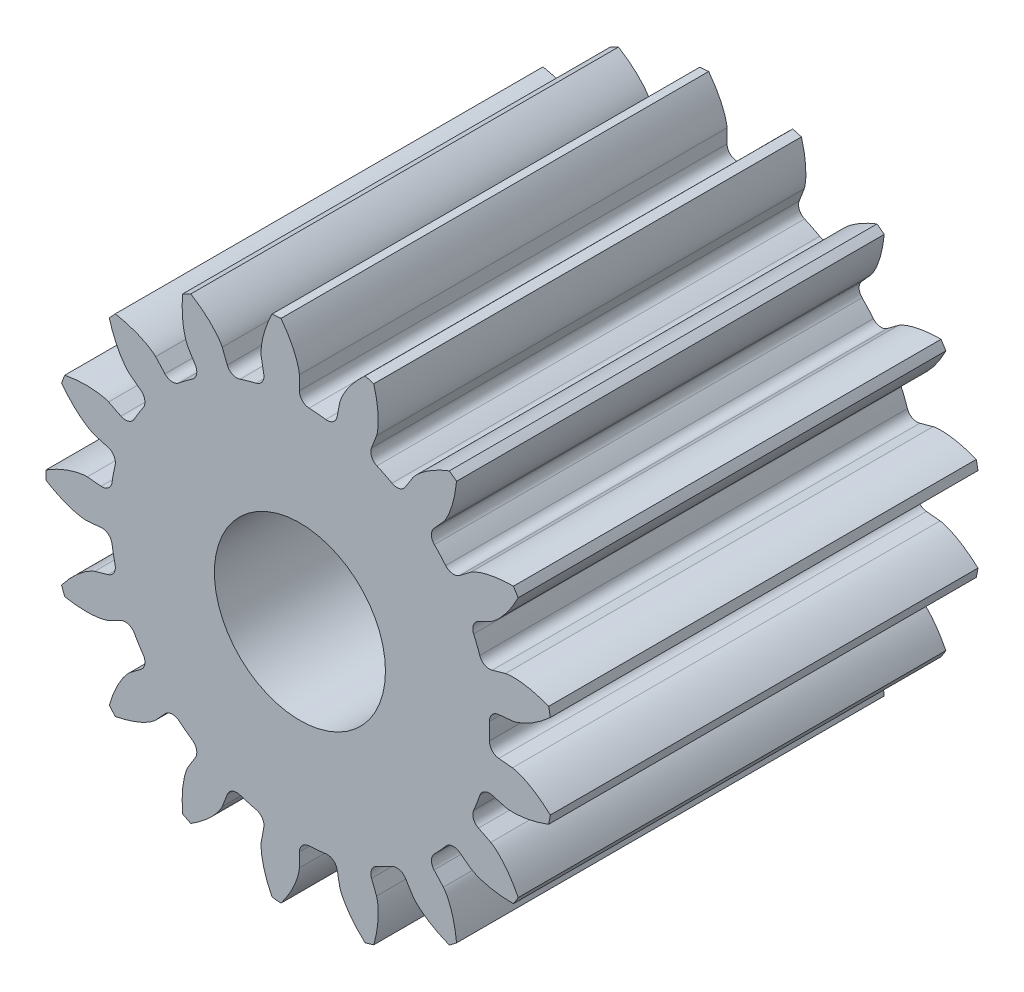
SolidWorks part; units mm, degrees
ref_plane "Front Plane" through (0, 0, 0) normal (0, 0, 1) x (1, 0, 0)
ref_plane "Top Plane" through (0, 0, 0) normal (0, 1, 0) x (1, 0, 0)
ref_plane "Right Plane" through (0, 0, 0) normal (1, 0, 0) x (0, 0, -1)
ref_axis "Gear Axis" through (0, 0, -0.2501) along (0, 0, 1)
sketch "Blank Sketch" plane through (0, 0, 0) normal (0, 0, 1) x (1, 0, 0)
  circle A0 centre (0, 0) radius 11.875
  dimension "OD" = 23.75
extrude "Blank" add sketch "Blank Sketch" along normal blind 20
sketch "Tooth Space Sketch" plane through (0, 0, 0) normal (0, 0, 1) x (1, 0, 0)
  line L0 (9.9391, 0.9485) -> (9.2957, 0.8871)
  line L1 (9.9391, -0.9485) -> (9.2957, -0.8871)
  line L2 (12.7424, 3.1457) -> (12.7424, -3.1457)
  arc A0 (9.2957, 0.8871) -> (8.8663, 0.3932) centre (9.3408, 0.4142) ccw
  arc A1 (8.8663, -0.3932) -> (9.2957, -0.8871) centre (9.3408, -0.4142) ccw
  arc A2 (8.8663, -0.3932) -> (8.8663, 0.3932) centre (0, 0) ccw
  spline S0 degree 4 poles (9.9391, 0.9485) (9.9444, 0.9491) (9.9594, 0.9511) (9.9875, 0.9561) (10.033, 0.9658) (10.0906, 0.9807) (10.1644, 1.0027) (10.2505, 1.0321) (10.344, 1.0681) (10.4445, 1.1112) (10.5435, 1.1577) (10.6412, 1.2072) (10.7373, 1.2593) (10.8523, 1.3258) (10.9883, 1.4101) (11.1441, 1.5151) (11.3169, 1.6419) (11.4885, 1.7791) (11.6537, 1.9206) (11.816, 2.0708) (11.9698, 2.2212) (12.1246, 2.3846) (12.2649, 2.5391) (12.4162, 2.7198) (12.5367, 2.8679) (12.6891, 3.071) (12.7772, 3.1933) (12.878, 3.3391) (12.9216, 3.4052) (12.9484, 3.4459) knots 0 0 0 0 0 0.005377 0.015084 0.028532 0.04661 0.064855 0.092111 0.119476 0.146842 0.174209 0.201575 0.228941 0.256307 0.307035 0.361767 0.4165 0.471232 0.525964 0.580697 0.635429 0.690161 0.744894 0.799626 0.854358 0.909091 0.954545 1 1 1 1 1 construction
  spline S1 degree 4 poles (9.9391, 0.9485) (9.9444, 0.9491) (9.9594, 0.9511) (9.9875, 0.9561) (10.033, 0.9658) (10.0906, 0.9807) (10.1644, 1.0027) (10.2505, 1.0321) (10.344, 1.0681) (10.4445, 1.1112) (10.5435, 1.1577) (10.6412, 1.2072) (10.7373, 1.2593) (10.8523, 1.3258) (10.9883, 1.4101) (11.1441, 1.5151) (11.3169, 1.6419) (11.4885, 1.7791) (11.6537, 1.9206) (11.816, 2.0708) (11.9698, 2.2212) (12.1246, 2.3846) (12.2649, 2.5391) (12.4162, 2.7198) (12.5367, 2.8679) (12.6561, 3.027) (12.7135, 3.1053) (12.7424, 3.1457) knots 0 0 0 0 0 0.005377 0.015084 0.028532 0.04661 0.064855 0.092111 0.119476 0.146842 0.174209 0.201575 0.228941 0.256307 0.307035 0.361767 0.4165 0.471232 0.525964 0.580697 0.635429 0.690161 0.744894 0.799626 0.854358 0.909091 0.909091 0.909091 0.909091 0.909091
  spline S2 degree 4 poles (9.9391, -0.9485) (9.9444, -0.9491) (9.9594, -0.9511) (9.9875, -0.9561) (10.033, -0.9658) (10.0906, -0.9807) (10.1644, -1.0027) (10.2505, -1.0321) (10.344, -1.0681) (10.4445, -1.1112) (10.5435, -1.1577) (10.6412, -1.2072) (10.7373, -1.2593) (10.8523, -1.3258) (10.9883, -1.4101) (11.1441, -1.5151) (11.3169, -1.6419) (11.4885, -1.7791) (11.6537, -1.9206) (11.816, -2.0708) (11.9698, -2.2212) (12.1246, -2.3846) (12.2649, -2.5391) (12.4162, -2.7198) (12.5367, -2.8679) (12.6891, -3.071) (12.7772, -3.1933) (12.878, -3.3391) (12.9216, -3.4052) (12.9484, -3.4459) knots 0 0 0 0 0 0.005377 0.015084 0.028532 0.04661 0.064855 0.092111 0.119476 0.146842 0.174209 0.201575 0.228941 0.256307 0.307035 0.361767 0.4165 0.471232 0.525964 0.580697 0.635429 0.690161 0.744894 0.799626 0.854358 0.909091 0.954545 1 1 1 1 1 construction
  spline S3 degree 4 poles (9.9391, -0.9485) (9.9444, -0.9491) (9.9594, -0.9511) (9.9875, -0.9561) (10.033, -0.9658) (10.0906, -0.9807) (10.1644, -1.0027) (10.2505, -1.0321) (10.344, -1.0681) (10.4445, -1.1112) (10.5435, -1.1577) (10.6412, -1.2072) (10.7373, -1.2593) (10.8523, -1.3258) (10.9883, -1.4101) (11.1441, -1.5151) (11.3169, -1.6419) (11.4885, -1.7791) (11.6537, -1.9206) (11.816, -2.0708) (11.9698, -2.2212) (12.1246, -2.3846) (12.2649, -2.5391) (12.4162, -2.7198) (12.5367, -2.8679) (12.6561, -3.027) (12.7135, -3.1053) (12.7424, -3.1457) knots 0 0 0 0 0 0.005377 0.015084 0.028532 0.04661 0.064855 0.092111 0.119476 0.146842 0.174209 0.201575 0.228941 0.256307 0.307035 0.361767 0.4165 0.471232 0.525964 0.580697 0.635429 0.690161 0.744894 0.799626 0.854358 0.909091 0.909091 0.909091 0.909091 0.909091
  dimension "Root" = 8.875
  dimension "Fillet" = 0.475
extrude "Tooth Space" cut sketch "Tooth Space Sketch" against normal through all both and the other way through all both
pattern_circular "Teeth" count 17 over 360 about axis through (0, 0, -0.2501) along (0, 0, 1) of "Tooth Space"
sketch "Bore Sketch" plane through (0, 0, 0) normal (0, 0, 1) x (1, 0, 0)
  circle A0 centre (0, 0) radius 4
  dimension "Bore" = 8
extrude "Bore" cut sketch "Bore Sketch" against normal through all both and the other way through all both
equation "\"No. of Teeth\"= 17"
equation "\"Module\"= 1.25"
equation "\"Bore Diameter\"= 8"
equation "\"Pressure Angle\"= 20"
equation "\"Outer Diameter\"= ( \"No. of Teeth\" + 2 ) * \"Module\""
equation "\"Pitch Diameter\"= \"No. of Teeth\" * \"Module\""
equation "\"Backlash\"= 0.3 * \"Module\""
equation "\"Arc Length\"= ( ( \"Module\" * pi ) / 2 + \"Backlash\" )"
equation "\"Fillet Radius\"= 0.38 * \"Module\""
equation "\"Tooth Depth\"= IIF ( \"Module\" <= 1.25 , \"Module\" * 2.4 , \"Module\" * 2.25 )"
equation "\"Face Width\"= 20"
equation "\"Root Diameter\"= \"Outer Diameter\" - 2 * \"Tooth Depth\""
equation "\"Base Diameter\"= \"Pitch Diameter\" * cos ( \"Pressure Angle\" )"
equation "\"Base Radius\"= \"Base Diameter\" / 2"
equation "\"Tooth Thickness\"= \"Module\" * pi - \"Arc Length\""
equation "\"Half Space Angle\"= ( \"Arc Length\" / \"Pitch Diameter\" ) * 180 / pi"
equation "\"Involute Fn\"= tan ( \"Pressure Angle\" ) - \"Pressure Angle\" * pi / 180"
equation "\"Flank Offset\"= \"Arc Length\" / \"Pitch Diameter\" - \"Involute Fn\""
equation "\"Tip Cap Diameter\"= \"Outer Diameter\" + 2 * \"Module\""
equation "\"Flank Start Diameter\"= IIF ( \"Base Diameter\" >= ( \"Root Diameter\" + 3 * \"Fillet Radius\" ) , \"Base Diameter\" , \"Root Diameter\" + 3 * \"Fillet Radius\" )"
equation "\"Involute t1\"= ( abs ( ( \"Flank Start Diameter\" / \"Base Diameter\" ) ^ 2 - 1 ) ) ^ 0.5"
equation "\"Involute t2\"= ( abs ( ( \"Tip Cap Diameter\" / \"Base Diameter\" ) ^ 2 - 1 ) ) ^ 0.5"
equation "\"Flank Arc Radius\"= ( \"Pitch Diameter\" / 2 ) * sin ( \"Pressure Angle\" )"
equation "\"Flank Centre Angle\"= \"Half Space Angle\" + \"Pressure Angle\""
equation "\"OD@Blank Sketch\"= \"Outer Diameter\""
equation "\"Width@Blank\"= \"Face Width\""
equation "\"Root@Tooth Space Sketch\"= \"Root Diameter\" / 2"
equation "\"Fillet@Tooth Space Sketch\"= \"Fillet Radius\""
equation "\"Count@Teeth\"= \"No. of Teeth\""
equation "\"Bore@Bore Sketch\"= \"Bore Diameter\""
